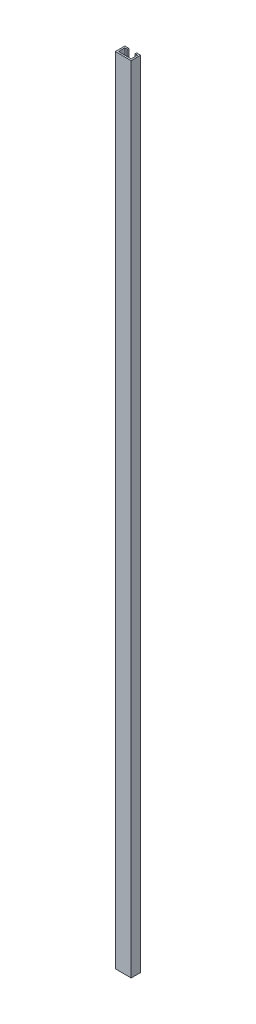
SolidWorks part; units mm, degrees
ref_plane "前视基准面" through (0, 0, 0) normal (0, 0, 1) x (1, 0, 0)
ref_plane "上视基准面" through (0, 0, 0) normal (0, 1, 0) x (1, 0, 0)
ref_plane "右视基准面" through (0, 0, 0) normal (1, 0, 0) x (0, 0, -1)
sketch "草图1" plane through (0, 0, 0) normal (0, 1, 0) x (1, 0, 0)
  line L0 (0, -6) -> (10, -6)
  line L1 (10, -6) -> (10, 0)
  line L2 (10, 0) -> (7.5, 0)
  line L3 (7.5, 0) -> (7.5, -1)
  line L4 (7.5, -1) -> (9, -1)
  line L5 (9, -1) -> (9, -5)
  line L6 (9, -5) -> (1, -5)
  line L7 (1, -5) -> (1, -1)
  line L8 (1, -1) -> (2.5, -1)
  line L9 (2.5, -1) -> (2.5, 0)
  line L10 (2.5, 0) -> (0, 0)
  line L11 (0, 0) -> (0, -6)
  line L12 (5, -5) -> (5, -6) construction
  line L13 (2.5, 0) -> (7.5, 0) construction
  line L14 (5, 0) -> (5, -5) construction
  dimension "D1" = 6
  dimension "D2" = 10
  dimension "D3" = 1
  dimension "D4" = 1
  dimension "D5" = 1
  dimension "D6" = 5
  dimension "D8" = 8
extrude "凸台-拉伸1" add sketch "草图1" along normal blind 500
